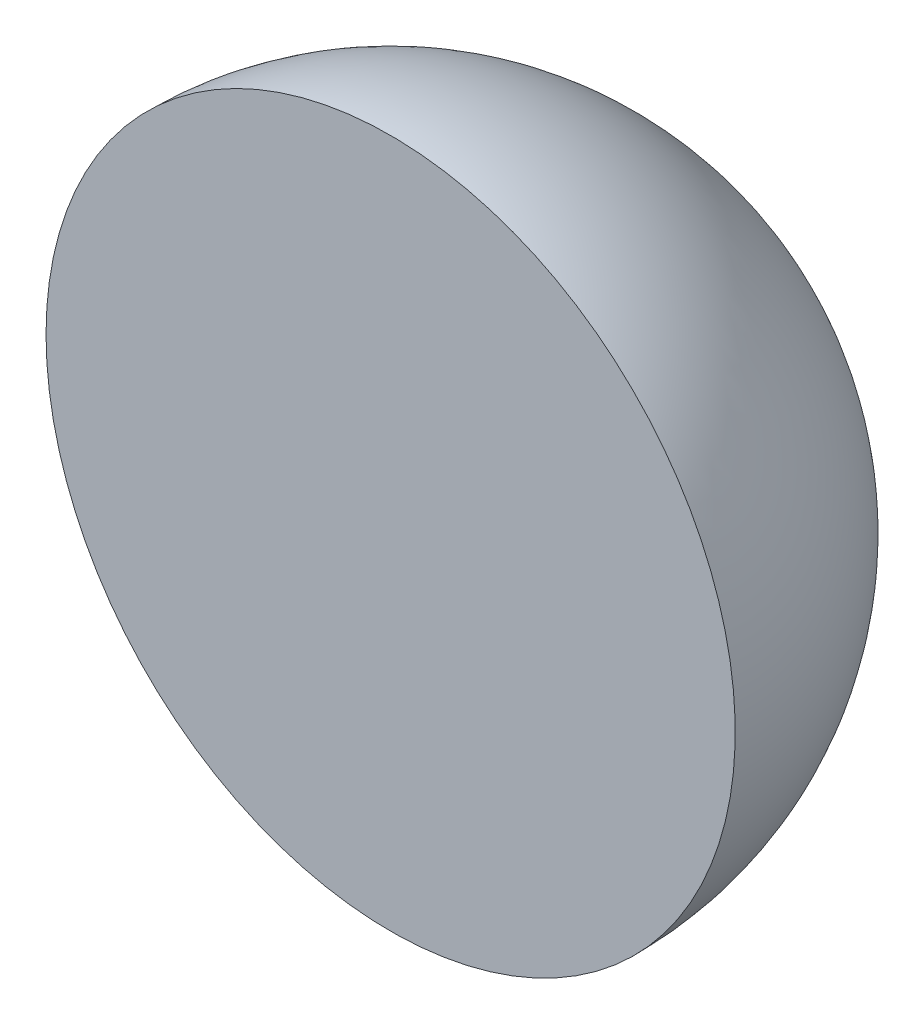
SolidWorks part; units mm, degrees
ref_plane "正面" through (0, 0, 0) normal (0, 0, 1) x (1, 0, 0)
ref_plane "平面" through (0, 0, 0) normal (0, 1, 0) x (1, 0, 0)
ref_plane "右側面" through (0, 0, 0) normal (1, 0, 0) x (0, 0, -1)
sketch "ｽｹｯﾁ1" plane through (0, 0, 0) normal (0, 1, 0) x (1, 0, 0)
  line L1 (4.9999, 0.0001) -> (-5.0001, 0.0001)
  line L3 (-0.0001, 4.9999) -> (-0.0001, 0.0001) construction
  arc A0 (4.9999, 0.0001) -> (-4.9999, 0) centre (0, 0) ccw
  dimension "D2" = 10
revolve "回転2" add sketch "ｽｹｯﾁ1" angle 360 about L3
